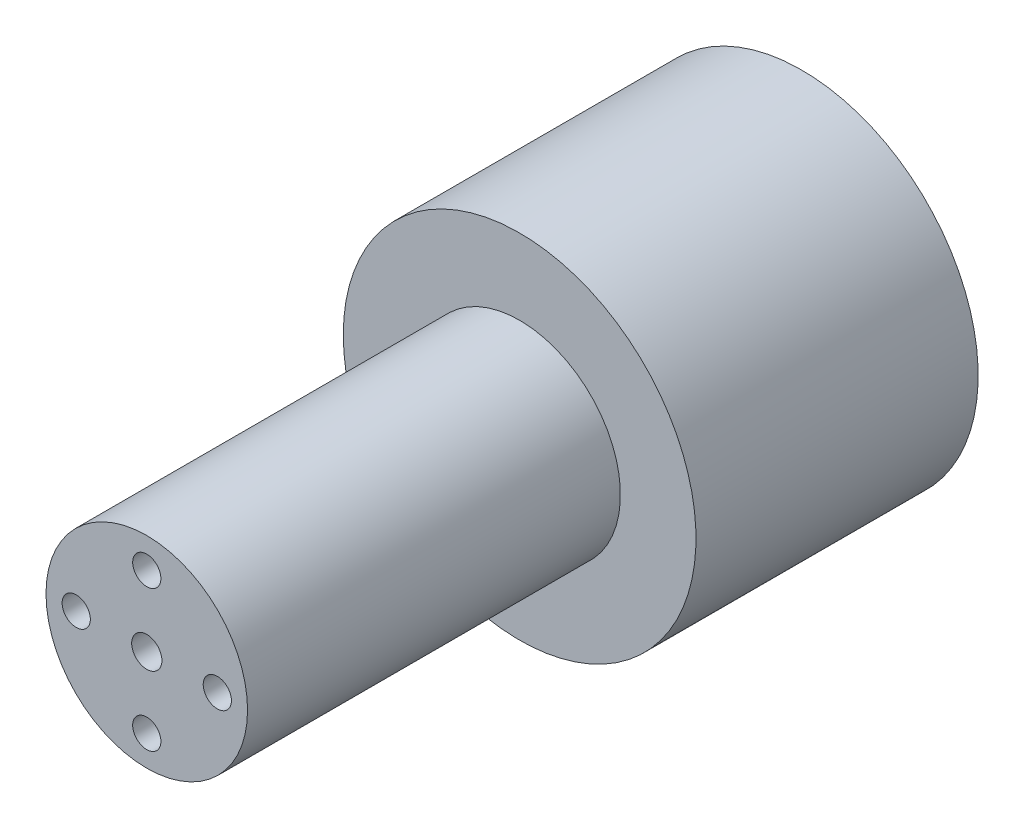
SolidWorks part; units mm, degrees
ref_plane "前视基准面" through (0, 0, 0) normal (0, 0, 1) x (1, 0, 0)
ref_plane "上视基准面" through (0, 0, 0) normal (0, 1, 0) x (1, 0, 0)
ref_plane "右视基准面" through (0, 0, 0) normal (1, 0, 0) x (0, 0, -1)
sketch "草图1" plane through (0, 0, 0) normal (0, 0, 1) x (1, 0, 0)
  circle A0 centre (0, 0) radius 10
  dimension "D1" = 20
extrude "凸台-拉伸1" add sketch "草图1" along normal blind 65
ref_plane "基准面1" through (-10, 0, 0) normal (-1, 0, 0) x (0, 0, 1)
sketch "草图2" plane through (-10, 0, 0) normal (-1, 0, 0) x (0, 0, 1)
  line L0 (30.6, 0) -> (37.6, 0) construction
  line L1 (30.6, 2.55) -> (37.6, 2.55)
  line L2 (30.6, -2.55) -> (37.6, -2.55)
  arc A0 (30.6, 2.55) -> (30.6, -2.55) centre (30.6, 0) ccw
  arc A1 (37.6, -2.55) -> (37.6, 2.55) centre (37.6, 0) ccw
  point P3 (34.1, 0)
  dimension "D2" = 2.55
  dimension "D1" = 30.6
  dimension "D3" = 7
extrude "切除-拉伸1" cut sketch "草图2" against normal blind 2.5
sketch "草图3" plane through (0, 0, 0) normal (0, 0, -1) x (-1, 0, 0)
  circle A0 centre (0, 0) radius 17.5
  dimension "D1" = 35
extrude "凸台-拉伸2" add sketch "草图3" against normal blind 28
sketch "草图4" plane through (0, 0, 65) normal (0, 0, 1) x (1, 0, 0)
  circle A1 centre (0, 7) radius 1.4
  circle A3 centre (7, 0) radius 1.4
  circle A5 centre (0, -7) radius 1.4
  circle A6 centre (0, 0) radius 7 construction
  circle A7 centre (-7, 0) radius 1.4
  dimension "D1" = 14
  dimension "D2" = 2.8
  dimension "D3" = 4
extrude "切除-拉伸2" cut sketch "草图4" against normal blind 3
sketch "草图5" plane through (0, 0, 65) normal (0, 0, 1) x (1, 0, 0)
  circle A0 centre (0, 0) radius 1.5
  dimension "D1" = 3
extrude "切除-拉伸3" cut sketch "草图5" against normal blind 3
